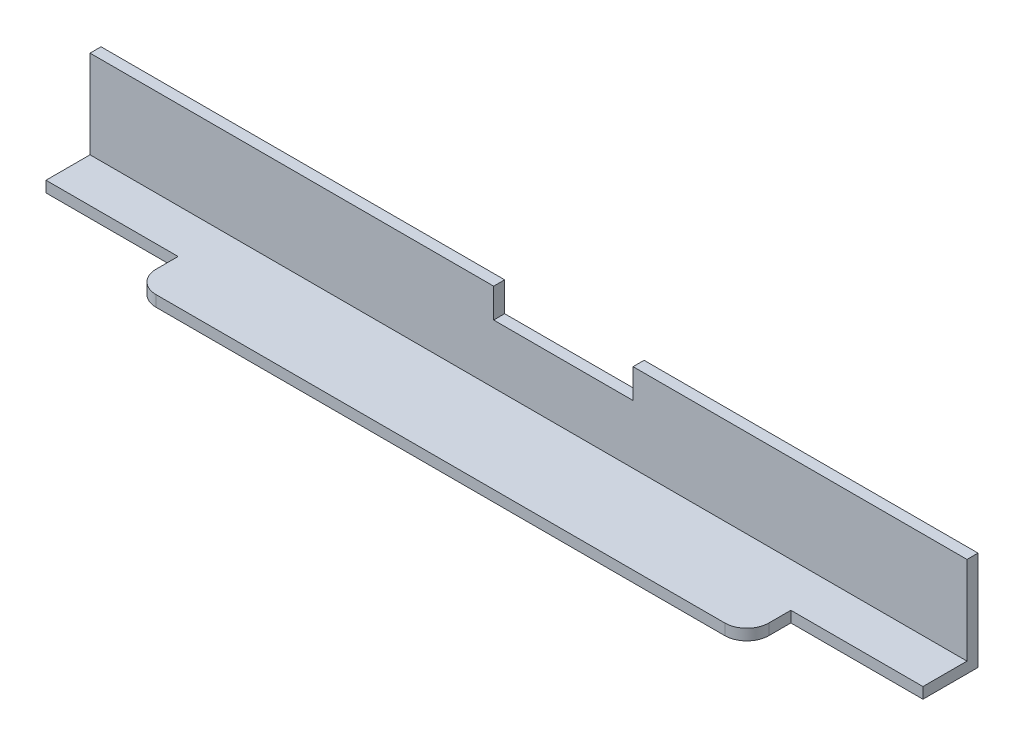
SolidWorks part; units mm, degrees
ref_plane "Front Plane" through (0, 0, 0) normal (0, 0, 1) x (1, 0, 0)
ref_plane "Top Plane" through (0, 0, 0) normal (0, 1, 0) x (1, 0, 0)
ref_plane "Right Plane" through (0, 0, 0) normal (1, 0, 0) x (0, 0, -1)
sketch "Sketch2" plane through (0, 0, 0) normal (0, 0, 1) x (1, 0, 0)
  line L1 (0, 0) -> (-239, 0)
  line L2 (0, 0) -> (0, -27)
  line L3 (0, -27) -> (-239, -27)
  line L4 (-239, 0) -> (-239, -27)
  dimension "D1" = 239
  dimension "D2" = 27
extrude "Boss-Extrude1" add sketch "Sketch2" along normal blind 3
sketch "Sketch3" plane through (0, 0, 3) normal (0, 0, 1) x (1, 0, 0)
  line L0 (0, -27) -> (0, 0) construction
  line L1 (-239, -27) -> (0, -27)
  line L2 (-239, -27) -> (-239, -24)
  line L3 (-239, -24) -> (0, -24)
  line L4 (0, -27) -> (0, -24)
  dimension "D1" = 3
extrude "Boss-Extrude2" add sketch "Sketch3" along normal blind 12
sketch "Sketch4" plane through (0, -24, 0) normal (0, 1, 0) x (1, 0, 0)
  line L0 (0, -15) -> (-239, -15) construction
  line L1 (-203, -15) -> (-36, -15)
  line L2 (-203, -15) -> (-203, -21)
  line L3 (-197, -27) -> (-42, -27)
  line L4 (-36, -15) -> (-36, -21)
  line L5 (-239, -15) -> (-239, -3) construction
  line L6 (0, -15) -> (0, -3) construction
  arc A0 (-42, -27) -> (-36, -21) centre (-42, -21) ccw
  arc A1 (-203, -21) -> (-197, -27) centre (-197, -21) ccw
  point P12 (-36, -27)
  dimension "D4" = 6
  dimension "D1" = 36
  dimension "D2" = 36
  dimension "D3" = 12
extrude "Boss-Extrude4" add sketch "Sketch4" against normal blind 3
sketch "Sketch5" plane through (0, 0, 0) normal (0, 0, -1) x (-1, 0, 0)
  line L0 (0, 0) -> (239, 0) construction
  line L1 (91, 0) -> (129, 0)
  line L2 (91, 0) -> (91, -8)
  line L3 (91, -8) -> (129, -8)
  line L4 (129, 0) -> (129, -8)
  line L5 (0, -27) -> (0, 0) construction
  dimension "D1" = 91
  dimension "D2" = 38
  dimension "D3" = 8
extrude "Cut-Extrude1" cut sketch "Sketch5" against normal blind 3
